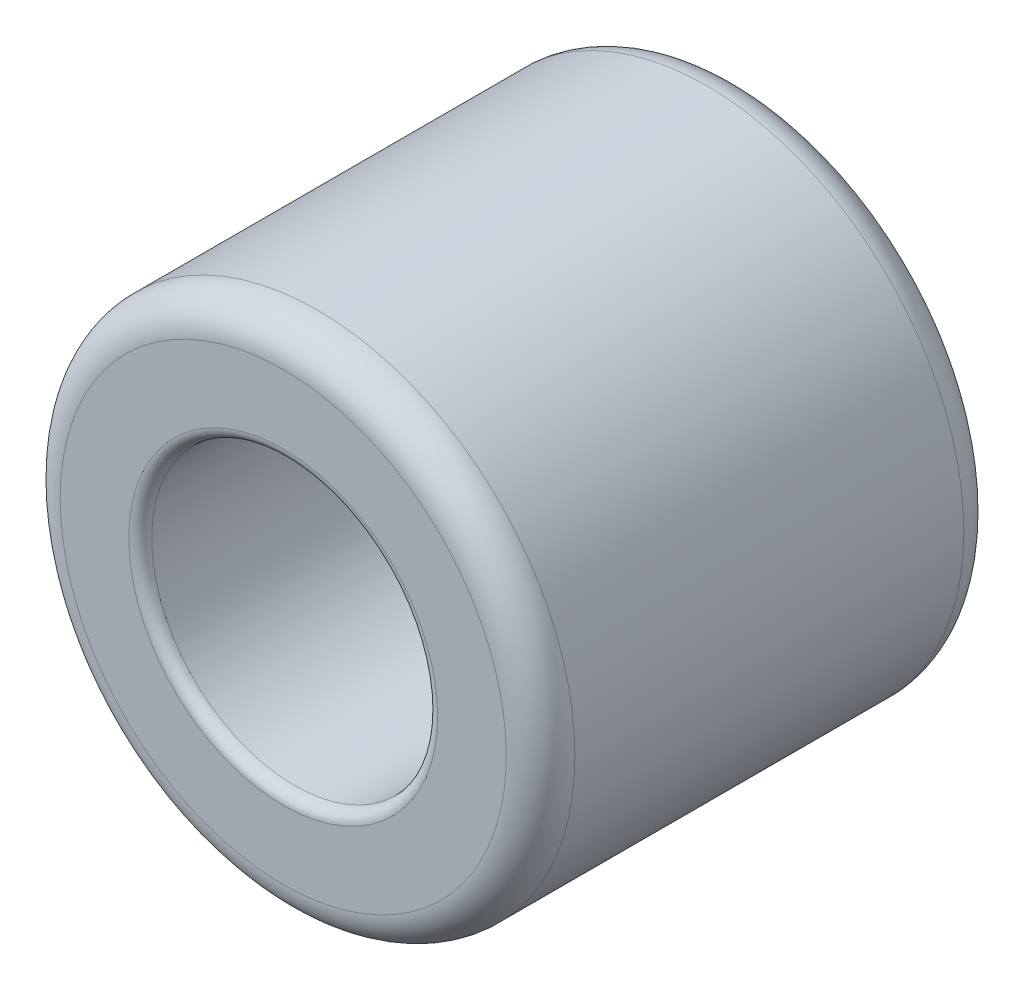
SolidWorks part; units mm, degrees
material "moto_blue_dark"
ref_plane "Front Plane" through (0, 0, 0) normal (0, 0, 1) x (1, 0, 0)
ref_plane "Top Plane" through (0, 0, 0) normal (0, 1, 0) x (1, 0, 0)
ref_plane "Right Plane" through (0, 0, 0) normal (1, 0, 0) x (0, 0, -1)
sketch "Sketch1" plane through (0, 0, 0) normal (0, 0, 1) x (1, 0, 0)
  circle A0 centre (0, 0) radius 12.5
  circle A1 centre (0, 0) radius 22.5
  circle A2 centre (0, 0) radius 7.5
  circle A3 centre (0, 0) radius 2.5
  dimension "D1" = 25
  dimension "D3" = 5
  dimension "D4" = 15
  dimension "D2" = 10
extrude "Boss-Extrude1" add sketch "Sketch1" along normal mid plane 40 contours A1 A0
fillet "Fillet1" radius 3 2 edges at (22.5, 0, -20) (22.5, 0, 20)
fillet "Fillet2" radius 1 2 edges at (12.5, 0, -20) (12.5, 0, 20)
